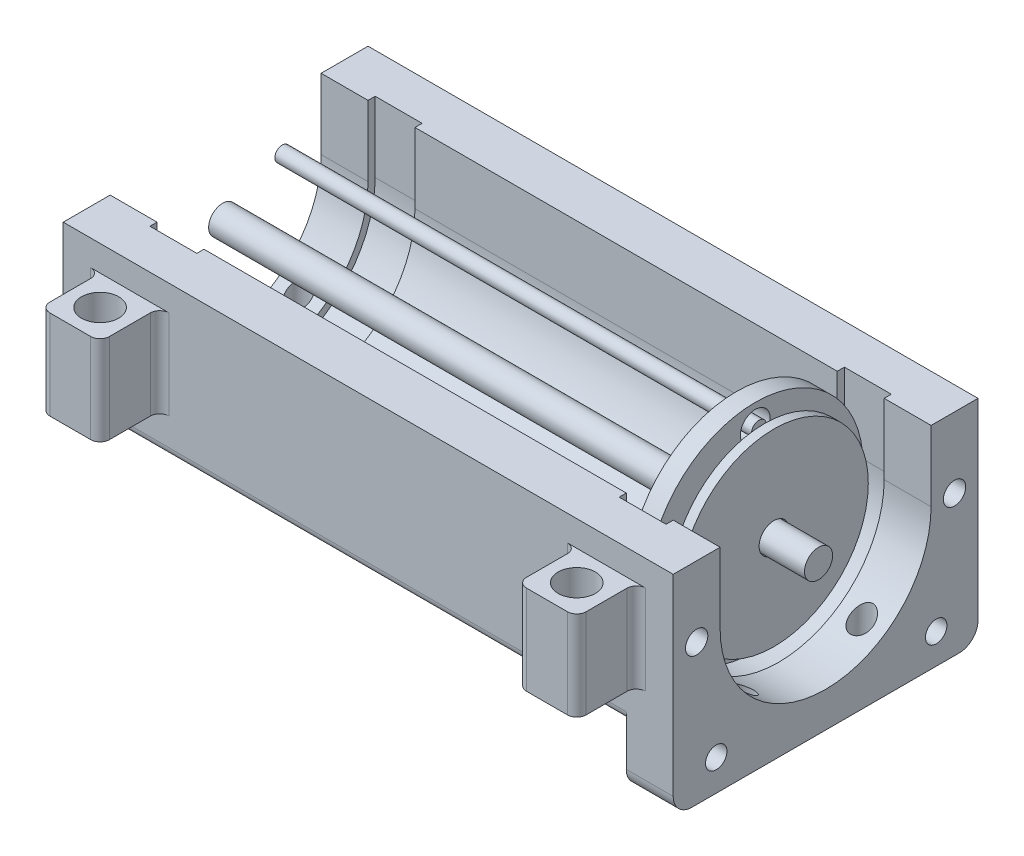
SolidWorks part; units mm, degrees
ref_plane "Front Plane" through (0, 0, 0) normal (0, 0, 1) x (1, 0, 0)
ref_plane "Top Plane" through (0, 0, 0) normal (0, 1, 0) x (1, 0, 0)
ref_plane "Right Plane" through (0, 0, 0) normal (1, 0, 0) x (0, 0, -1)
sketch "Sketch1" plane through (0, 0, 0) normal (1, 0, 0) x (0, 0, -1)
  line L0 (-22.4812, 0) -> (-22.4812, 15)
  line L1 (22.4812, 0) -> (22.4812, 15)
  line L2 (-23.3122, -17.371) -> (-30.4812, -17.371)
  line L3 (0, 0) -> (0, 31.7138) construction
  line L4 (-15.3123, -30) -> (15.4297, -30)
  line L5 (-17.3123, -23.371) -> (-17.3123, -28)
  line L6 (17.4297, -23.371) -> (17.4297, -28)
  line L7 (23.4297, -17.371) -> (30.0587, -17.371)
  line L8 (-32.4812, 15) -> (-32.4812, -15.371)
  line L9 (22.4812, 15) -> (32.4812, 15)
  line L10 (-22.4812, 15) -> (-32.4812, 15)
  line L11 (32.4812, 15) -> (32.4813, -15.371)
  line L13 (30.4812, -17.371) -> (30.0587, -17.371)
  line L14 (-27.4812, 15) -> (-27.4813, 0) construction
  line L15 (27.4812, 15) -> (27.4812, 0) construction
  arc A0 (-22.4812, 0) -> (22.4812, 0) centre (0, 0) ccw
  arc A1 (-23.3122, -17.371) -> (-17.3123, -23.371) centre (-23.3122, -23.371) cw
  arc A2 (17.4297, -23.371) -> (23.4297, -17.371) centre (23.4297, -23.371) cw
  arc A3 (-30.4812, -17.371) -> (-32.4812, -15.371) centre (-30.4812, -15.371) cw
  arc A4 (32.4813, -15.371) -> (30.4812, -17.371) centre (30.4812, -15.371) cw
  arc A5 (-17.3123, -28) -> (-15.3123, -30) centre (-15.3123, -28) ccw
  arc A6 (17.4297, -28) -> (15.4297, -30) centre (15.4297, -28) cw
  circle A7 centre (0, 0) radius 27.4813 construction
  circle A8 centre (-27.4813, 0) radius 2.3813
  circle A9 centre (27.4812, 0) radius 2.3813
  dimension "D1" = 6
  dimension "D2" = 6
  dimension "D3" = 2
  dimension "D4" = 2
  dimension "D5" = 2
  dimension "D6" = 10
  dimension "D7" = 54.9625
  dimension "D8" = 4.7625
extrude "Boss-Extrude1" add sketch "Sketch1" along normal mid plane 90
ref_plane "Plane1" through (45, 0, 0) normal (1, 0, 0) x (0, 0, -1)
ref_plane "Plane2" through (46, 0, 0) normal (1, 0, 0) x (0, 0, -1)
sketch "Sketch3" plane through (46, 0, 0) normal (1, 0, 0) x (0, 0, -1)
  line L0 (0, 0) -> (0, 1.0694) construction
  circle A0 centre (0, 0) radius 3.175
  circle A1 centre (0, 18.5125) radius 1.5875 construction
  circle A2 centre (0, 18.5125) radius 3.175
  circle A3 centre (0, 0) radius 23
  circle A4 centre (-18.5125, 0) radius 1.5875 construction
  circle A5 centre (-18.5125, 0) radius 3.175
  circle A6 centre (0, -18.5125) radius 1.5875 construction
  circle A7 centre (0, -18.5125) radius 3.175
  circle A8 centre (18.5125, 0) radius 1.5875 construction
  circle A9 centre (18.5125, 0) radius 3.175
  circle A10 centre (0, 0) radius 20.1 construction
  circle A11 centre (0, 0) radius 18.5125 construction
  dimension "D1" = 6.35
  dimension "D2" = 3.175
  dimension "D3" = 6.35
  dimension "D4" = 46
  dimension "D5" = 40.2
  dimension "D6" = 37.025
extrude "Boss-Extrude2" add sketch "Sketch3" along normal blind 4 separate body
ref_plane "Sketch16" through (52, 0, 0) normal (1, 0, 0) x (0, 0, -1)
sketch "Sketch17" plane through (52, 0, 0) normal (1, 0, 0) x (0, 0, -1)
  circle A1 centre (0, 0) radius 3.175
  circle A2 centre (0, 0) radius 20.1
  dimension "D1" = 6.35
extrude "Boss-Extrude4" add sketch "Sketch17" along normal blind 2 separate body
sketch "Sketch19" plane through (0, 0, 0) normal (1, 0, 0) x (0, 0, -1)
  circle A0 centre (0, 0) radius 3
  circle A1 centre (0, 0) radius 18.5125 construction
  dimension "D1" = 37.025
  dimension "D2" = 6
extrude "Boss-Extrude6" add sketch "Sketch19" along normal mid plane 127
sketch "Sketch20" plane through (0, 0, 0) normal (1, 0, 0) x (0, 0, -1)
  circle A0 centre (0, 0) radius 18.5125 construction
  circle A1 centre (0, 18.5125) radius 1.5875
  circle A2 centre (18.5125, 0) radius 1.5875
  circle A3 centre (0, -18.5125) radius 1.5875
  circle A4 centre (-18.5125, 0) radius 1.5875
  dimension "D1" = 37.025
  dimension "D2" = 3.175
extrude "Boss-Extrude7" add sketch "Sketch20" along normal mid plane 101.6 separate body
sketch "Sketch21" plane through (45, 0, 0) normal (1, 0, 0) x (0, 0, -1)
  line L0 (-24, 0) -> (-24, 15)
  line L1 (24, 0) -> (24, 15)
  line L2 (-23.3122, -17.371) -> (-30.4812, -17.371)
  line L3 (0, 0) -> (0, 31.7138) construction
  line L4 (-15.3123, -30) -> (15.4297, -30)
  line L5 (-17.3123, -23.371) -> (-17.3123, -28)
  line L6 (17.4297, -23.371) -> (17.4297, -28)
  line L7 (23.4297, -17.371) -> (30.0587, -17.371)
  line L8 (-32.4812, 15) -> (-32.4812, -15.371)
  line L9 (24, 15) -> (32.4812, 15)
  line L10 (-24, 15) -> (-32.4812, 15)
  line L11 (32.4812, 15) -> (32.4813, -15.371)
  line L12 (-24, 0) -> (24, 0) construction
  line L13 (30.4812, -17.371) -> (30.0587, -17.371)
  line L14 (0, 0) -> (0, -24) construction
  arc A0 (-24, 0) -> (24, 0) centre (0, 0) ccw
  arc A1 (-23.3122, -17.371) -> (-17.3123, -23.371) centre (-23.3122, -23.371) cw
  arc A2 (17.4297, -23.371) -> (23.4297, -17.371) centre (23.4297, -23.371) cw
  arc A3 (-30.4812, -17.371) -> (-32.4812, -15.371) centre (-30.4812, -15.371) cw
  arc A4 (32.4813, -15.371) -> (30.4812, -17.371) centre (30.4812, -15.371) cw
  arc A5 (-17.3123, -28) -> (-15.3123, -30) centre (-15.3123, -28) ccw
  arc A6 (17.4297, -28) -> (15.4297, -30) centre (15.4297, -28) cw
  circle A7 centre (0, 0) radius 23 construction
  circle A8 centre (0, 0) radius 27.4812 construction
  circle A9 centre (-27.4813, 0) radius 2.3813
  circle A10 centre (27.4812, 0) radius 2.3812
  dimension "D1" = 6
  dimension "D2" = 6
  dimension "D3" = 2
  dimension "D4" = 2
  dimension "D5" = 2
  dimension "D6" = 54.9625
  dimension "D7" = 46
extrude "Boss-Extrude8" add sketch "Sketch21" along normal blind 10
ref_plane "Plane5" through (55, 0, 0) normal (1, 0, 0) x (0, 0, -1)
sketch "Sketch23" plane through (55, 0, 0) normal (1, 0, 0) x (0, 0, -1)
  line L0 (-22.4812, 0) -> (-22.4812, 15)
  line L1 (22.4812, 0) -> (22.4812, 15)
  line L3 (0, 0) -> (0, 31.7138) construction
  line L4 (-28.4812, -30) -> (28.4812, -30)
  line L8 (-32.4812, 15) -> (-32.4813, -26)
  line L9 (22.4812, 15) -> (32.4812, 15)
  line L10 (-22.4812, 15) -> (-32.4812, 15)
  line L11 (32.4812, 15) -> (32.4813, -26)
  line L14 (23.5712, 23.5712) -> (-23.5712, 23.5712) construction
  line L15 (23.5712, 23.5712) -> (23.5712, -23.5712) construction
  line L16 (23.5712, -23.5712) -> (-23.5712, -23.5712) construction
  line L17 (-23.5712, 23.5712) -> (-23.5712, -23.5712) construction
  line L18 (23.5712, 23.5712) -> (-23.5712, -23.5712) construction
  line L19 (23.5712, -23.5712) -> (-23.5712, 23.5712) construction
  arc A0 (-22.4812, 0) -> (22.4812, 0) centre (0, 0) ccw
  arc A1 (28.4812, -30) -> (32.4813, -26) centre (28.4813, -26) ccw
  arc A3 (-28.4812, -30) -> (-32.4813, -26) centre (-28.4813, -26) cw
  circle A7 centre (-27.4813, 0) radius 2.3813
  circle A8 centre (27.4812, 0) radius 2.3812
  circle A9 centre (0, 0) radius 22.4812 construction
  circle A10 centre (-23.3122, -23.371) radius 2.286
  circle A11 centre (23.5712, -23.5712) radius 2.286
  dimension "D2" = 4
  dimension "D3" = 4
  dimension "D6" = 10
  dimension "D7" = 44.9625
  dimension "D10" = 4.572
  dimension "D8" = 47.1424
  dimension "D9" = 47.1424
extrude "Boss-Extrude9" add sketch "Sketch23" along normal blind 10
ref_plane "Plane6" through (0, -30, 0) normal (0, -1, 0) x (1, 0, 0)
sketch "Sketch24" plane through (0, -30, 0) normal (0, -1, 0) x (1, 0, 0)
  line L0 (55, 0) -> (65, 0) construction
  line L1 (55, -24.75) -> (55, 24.75) construction
  line L2 (65, 28.4812) -> (65, -28.4812) construction
  line L3 (60, 12.7) -> (60, -12.7) construction
  circle A0 centre (60, 0) radius 12.7 construction
  circle A1 centre (60, 12.7) radius 2.3812
  circle A2 centre (60, -12.7) radius 2.3812
  dimension "D1" = 25.4
  dimension "D2" = 4.7625
extrude "Cut-Extrude1" cut sketch "Sketch24" against normal blind 50 contours A2 | A1
ref_plane "Plane7" through (-45, 0, 0) normal (-1, 0, 0) x (0, 0, 1)
sketch "Sketch25" plane through (-45, 0, 0) normal (-1, 0, 0) x (0, 0, 1)
  line L0 (-24, 0) -> (-24, 15)
  line L1 (24, 0) -> (24, 15)
  line L2 (-23.3122, -17.371) -> (-30.4812, -17.371)
  line L3 (0, 0) -> (0, 31.7138) construction
  line L4 (-15.3123, -30) -> (15.4297, -30)
  line L5 (-17.3123, -23.371) -> (-17.3123, -28)
  line L6 (17.4297, -23.371) -> (17.4297, -28)
  line L7 (23.4297, -17.371) -> (30.0587, -17.371)
  line L8 (-32.4812, 15) -> (-32.4812, -15.371)
  line L9 (24, 15) -> (32.4812, 15)
  line L10 (-24, 15) -> (-32.4812, 15)
  line L11 (32.4812, 15) -> (32.4813, -15.371)
  line L12 (-24, 0) -> (24, 0) construction
  line L13 (30.4812, -17.371) -> (30.0587, -17.371)
  line L14 (0, 0) -> (0, -24) construction
  arc A0 (-24, 0) -> (24, 0) centre (0, 0) ccw
  arc A1 (-23.3122, -17.371) -> (-17.3123, -23.371) centre (-23.3122, -23.371) cw
  arc A2 (17.4297, -23.371) -> (23.4297, -17.371) centre (23.4297, -23.371) cw
  arc A3 (-30.4812, -17.371) -> (-32.4812, -15.371) centre (-30.4812, -15.371) cw
  arc A4 (32.4813, -15.371) -> (30.4812, -17.371) centre (30.4812, -15.371) cw
  arc A5 (-17.3123, -28) -> (-15.3123, -30) centre (-15.3123, -28) ccw
  arc A6 (17.4297, -28) -> (15.4297, -30) centre (15.4297, -28) cw
  circle A7 centre (0, 0) radius 23 construction
  circle A8 centre (-27.4812, 0) radius 2.3813
  circle A9 centre (27.4813, 0) radius 2.3813
  dimension "D1" = 6
  dimension "D2" = 6
  dimension "D3" = 2
  dimension "D4" = 2
  dimension "D5" = 2
  dimension "D7" = 46
extrude "Boss-Extrude10" add sketch "Sketch25" along normal blind 10
ref_plane "Plane8" through (-55, 0, 0) normal (-1, 0, 0) x (0, 0, 1)
sketch "Sketch27" plane through (-55, 0, 0) normal (-1, 0, 0) x (0, 0, 1)
  line L0 (-22.4812, 0) -> (-22.4812, 15)
  line L1 (22.4812, 0) -> (22.4812, 15)
  line L2 (-23.3122, -17.371) -> (-30.4812, -17.371)
  line L3 (0, 0) -> (0, 31.7138) construction
  line L4 (-15.3123, -30) -> (15.4297, -30)
  line L5 (-17.3123, -23.371) -> (-17.3123, -28)
  line L6 (17.4297, -23.371) -> (17.4297, -28)
  line L7 (23.4297, -17.371) -> (30.0587, -17.371)
  line L8 (-32.4812, 15) -> (-32.4812, -15.371)
  line L9 (22.4812, 15) -> (32.4812, 15)
  line L10 (-22.4812, 15) -> (-32.4812, 15)
  line L11 (32.4812, 15) -> (32.4813, -15.371)
  line L13 (30.4812, -17.371) -> (30.0587, -17.371)
  arc A0 (-22.4812, 0) -> (22.4812, 0) centre (0, 0) ccw
  arc A1 (-23.3122, -17.371) -> (-17.3123, -23.371) centre (-23.3122, -23.371) cw
  arc A2 (17.4297, -23.371) -> (23.4297, -17.371) centre (23.4297, -23.371) cw
  arc A3 (-30.4812, -17.371) -> (-32.4812, -15.371) centre (-30.4812, -15.371) cw
  arc A4 (32.4813, -15.371) -> (30.4812, -17.371) centre (30.4812, -15.371) cw
  arc A5 (-17.3123, -28) -> (-15.3123, -30) centre (-15.3123, -28) ccw
  arc A6 (17.4297, -28) -> (15.4297, -30) centre (15.4297, -28) cw
  circle A7 centre (-27.4812, 0) radius 2.3813
  circle A8 centre (27.4813, 0) radius 2.3813
  dimension "D1" = 6
  dimension "D2" = 6
  dimension "D3" = 2
  dimension "D4" = 2
  dimension "D5" = 2
  dimension "D6" = 10
extrude "Boss-Extrude11" add sketch "Sketch27" along normal blind 10
mirror "Mirror6" about plane through (0, 0, 0) normal (1, 0, 0) of "Cut-Extrude1"
ref_plane "Plane9" through (0, 0, 32.4812) normal (0, 0, 1) x (1, 0, 0)
ref_plane "Plane10" through (0, 15, 0) normal (0, 1, 0) x (-1, 0, 0)
sketch "Sketch29" plane through (0, 0, 32.4812) normal (0, 0, 1) x (1, 0, 0)
  line L0 (63, 9.3126) -> (-63, 9.525) construction
  line L2 (63, -9.525) -> (-63, -9.525) construction
  line L4 (44.45, 9.525) -> (44.45, -9.525) construction
  line L5 (-63, 9.525) -> (63, 9.525)
  line L6 (-63, 9.525) -> (-63, -9.525)
  line L7 (-63, -9.525) -> (63, -9.525)
  line L8 (63, 9.525) -> (63, -9.525)
  line L9 (57.15, 9.525) -> (57.15, -9.525) construction
  line L11 (44.45, 9.525) -> (57.15, 9.525)
  line L12 (44.45, 9.525) -> (44.45, -9.525)
  line L13 (44.45, -9.525) -> (57.15, -9.525)
  line L14 (57.15, 9.525) -> (57.15, -9.525)
  circle A0 centre (0, 0) radius 50.8 construction
  circle A1 centre (50.8, 0) radius 6.35 construction
  dimension "D1" = 12.7
  dimension "D2" = 19.05
extrude "Boss-Extrude12" add sketch "Sketch29" along normal blind 12.7 contours L14 L5 L12 L7
sketch "Sketch30" plane through (0, 9.525, 0) normal (0, 1, 0) x (1, 0, 0)
  circle A0 centre (50.8, -38.8312) radius 3.9687
  dimension "D1" = 7.9375
extrude "Cut-Extrude2" cut sketch "Sketch30" against normal blind 40
mirror "Mirror7" about plane through (0, 0, 0) normal (1, 0, 0) of "Cut-Extrude2", "Boss-Extrude12"
fillet "Fillet1" radius 2 8 edges at (57.15, 0, 45.1812) (57.15, 0, 32.4812) (44.45, 0, 45.1812) (44.45, 0, 32.4812) (-57.15, 0, 45.1812) (-57.15, 0, 32.4812) (-44.45, 0, 45.1812) (-44.45, 0, 32.4812)
